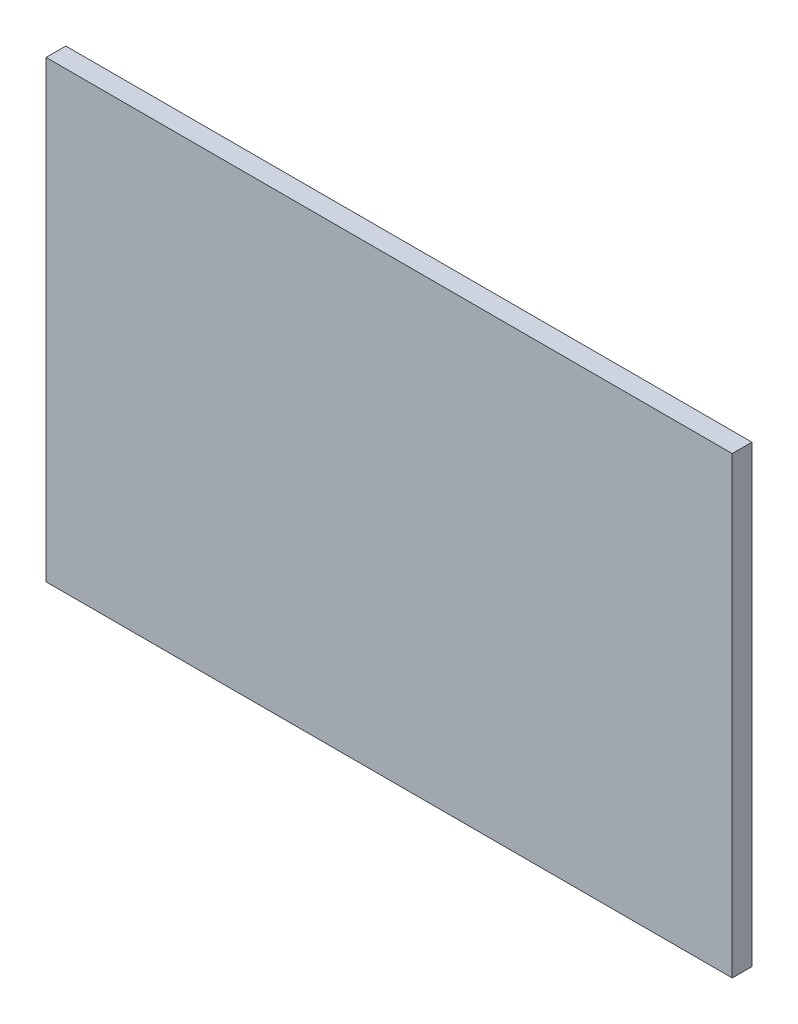
SolidWorks part; units mm, degrees
material "Pine"
ref_plane "Front Plane" through (0, 0, 0) normal (0, 0, 1) x (1, 0, 0)
ref_plane "Top Plane" through (0, 0, 0) normal (0, 1, 0) x (1, 0, 0)
ref_plane "Right Plane" through (0, 0, 0) normal (1, 0, 0) x (0, 0, -1)
sketch "Sketch5" plane through (0, 0, 0) normal (0, 0, 1) x (1, 0, 0)
  line L6 (0, 0) -> (417, 0)
  line L7 (0, 0) -> (0, 276)
  line L8 (0, 276) -> (417, 276)
  line L9 (417, 0) -> (417, 276)
  dimension "D1" = 417
  dimension "D2" = 276
extrude "Boss-Extrude3" add sketch "Sketch5" along normal blind 12 separate body
equation "\"LENGTH\" = 1000mm"
equation "\"PLY\"= 12mm"
equation "\"CENTER_BRACE_LENGTH\" = 393mm"
equation "\"PANEL_WIDTH\"= \"LENGTH\" - \"CENTER_BRACE_LENGTH\" * 2 - \"PLY\" * 4"
equation "\"D1@Boss-Extrude3\"=\"PLY\""
equation "\"D1@Sketch5\"=\"LENGTH\"/2 - \"PANEL_WIDTH\"/2"
